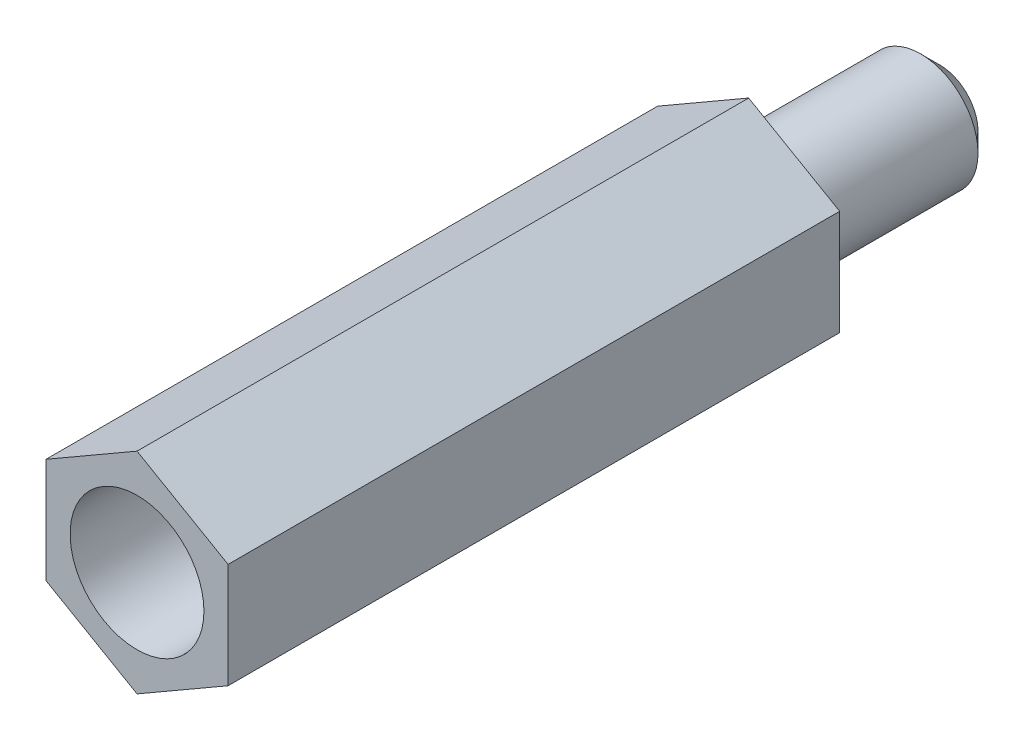
SolidWorks part; units mm, degrees
ref_plane "Front Plane" through (0, 0, 0) normal (0, 0, 1) x (1, 0, 0)
ref_plane "Top Plane" through (0, 0, 0) normal (0, 1, 0) x (1, 0, 0)
ref_plane "Right Plane" through (0, 0, 0) normal (1, 0, 0) x (0, 0, -1)
sketch "Sketch1" plane through (0, 0, 0) normal (0, 0, 1) x (1, 0, 0)
  line L1 (0, 2.75) -> (-2.3816, 1.375)
  line L2 (-2.3816, 1.375) -> (-2.3816, -1.375)
  line L3 (-2.3816, -1.375) -> (0, -2.75)
  line L4 (0, -2.75) -> (2.3816, -1.375)
  line L5 (2.3816, -1.375) -> (2.3816, 1.375)
  line L6 (2.3816, 1.375) -> (0, 2.75)
  circle A0 centre (0, 0) radius 2.75 construction
  circle A1 centre (0, 0) radius 2.3816 construction
  dimension "D1" = 5.5
extrude "Boss-Extrude1" add sketch "Sketch1" along normal blind 16
sketch "Sketch2" plane through (0, 0, 16) normal (0, 0, 1) x (1, 0, 0)
  circle A0 centre (0, 0) radius 1.75
extrude "Cut-Extrude1" cut sketch "Sketch2" against normal blind 8
sketch "Sketch3" plane through (0, 0, 0) normal (0, 0, -1) x (-1, 0, 0)
  circle A0 centre (0, 0) radius 1.5
extrude "Boss-Extrude2" add sketch "Sketch3" along normal blind 5
chamfer "Chamfer1" distance 0.5 angle 45 1 edges at (-1.5, 0, -5)
